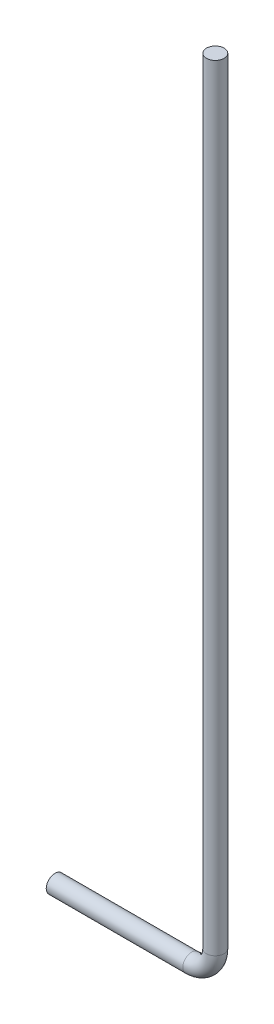
SolidWorks part; units mm, degrees
ref_plane "Front Plane" through (0, 0, 0) normal (0, 0, 1) x (1, 0, 0)
ref_plane "Top Plane" through (0, 0, 0) normal (0, 1, 0) x (1, 0, 0)
ref_plane "Right Plane" through (0, 0, 0) normal (1, 0, 0) x (0, 0, -1)
sketch "Sketch1" plane through (0, 0, 0) normal (0, 0, 1) x (1, 0, 0)
  line L0 (0, 300) -> (0, -50.8)
  line L1 (-10.7156, -61.5156) -> (-72.479, -61.5156)
  arc A0 (0, -50.8) -> (-10.7156, -61.5156) centre (-10.7156, -50.8) cw
  dimension "D1" = 10.7156
  dimension "D2" = 72.479
  dimension "D3" = 300
  dimension "D4" = 50.8
ref_plane "Plane1" through (0, 300, 0) normal (0, 1, 0) x (1, 0, 0)
sketch "Sketch2" plane through (0, 300, 0) normal (0, 1, 0) x (1, 0, 0)
  circle A0 centre (0, 0) radius 4
  dimension "D1" = 8
sweep "Sweep1" add profiles "Sketch2" path "Sketch1"
